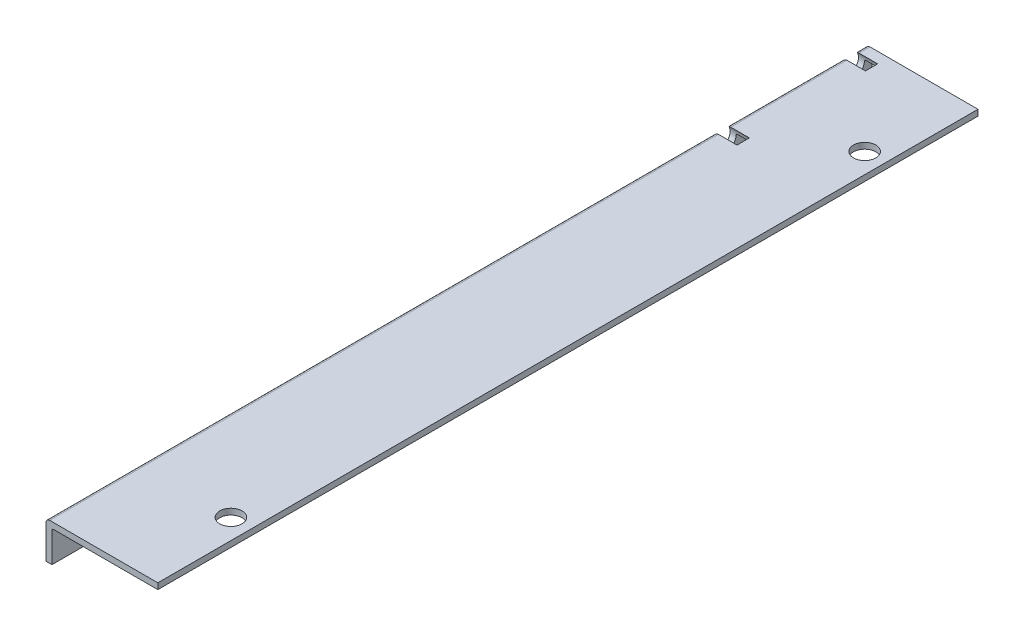
SolidWorks part; units mm, degrees
ref_plane "前视基准面" through (0, 0, 0) normal (0, 0, 1) x (1, 0, 0)
ref_plane "上视基准面" through (0, 0, 0) normal (0, 1, 0) x (1, 0, 0)
ref_plane "右视基准面" through (0, 0, 0) normal (1, 0, 0) x (0, 0, -1)
sketch "草图1" plane through (0, 0, 0) normal (0, 0, 1) x (1, 0, 0)
  line L0 (0, 0) -> (0, 45)
  line L1 (5, 50) -> (150, 50)
  line L2 (8, 0) -> (8, 40)
  line L3 (10, 42) -> (150, 42)
  line L4 (0, 0) -> (8, 0)
  line L5 (150, 50) -> (150, 42)
  line L6 (0, 0) -> (0, 50) construction
  line L7 (0, 50) -> (150, 50) construction
  line L8 (8, 0) -> (8, 42) construction
  line L9 (8, 42) -> (150, 42) construction
  arc A0 (0, 45) -> (5, 50) centre (5, 45) cw
  arc A1 (8, 40) -> (10, 42) centre (10, 40) cw
  point P10 (0, 50)
  dimension "D4" = 5
  dimension "D5" = 2
  dimension "D1" = 50
  dimension "D2" = 150
  dimension "D3" = 8
extrude "凸台-拉伸1" add sketch "草图1" along normal blind 1100
sketch "草图2" plane through (0, 50, 0) normal (0, 1, 0) x (1, 0, 0)
  circle A0 centre (123, -975) radius 15
  circle A1 centre (123, -125) radius 15
extrude "切除-拉伸1" cut sketch "草图2" against normal blind 10
sketch "草图3" plane through (0, 0, 0) normal (-1, 0, 0) x (0, 0, 1)
  circle A0 centre (283.5433, 25.0225) radius 7
  circle A1 centre (140.9394, 19.7047) radius 7
  circle A2 centre (22.7625, 40.5424) radius 7
  circle A3 centre (194.9106, 40.6509) radius 7
  circle A4 centre (81.851, 30.1235) radius 7
  dimension "D1" = 14
  dimension "D2" = 14
  dimension "D3" = 14
  dimension "D4" = 14
  dimension "D5" = 14
extrude "切除-拉伸2" cut sketch "草图3" against normal blind 10
sketch "草图4" plane through (0, 0, 0) normal (-1, 0, 0) x (0, 0, 1)
  circle A0 centre (22.7625, 40.5424) radius 12.5
  circle A1 centre (194.9106, 40.6509) radius 12.5
  dimension "D1" = 25
  dimension "D2" = 25
extrude "切除-拉伸3" cut sketch "草图4" against normal blind 30
sketch "草图5" plane through (0, 0, 0) normal (-1, 0, 0) x (0, 0, 1)
  line L0 (283.5433, 25.0225) -> (960.8976, 25.0225) construction
  line L1 (1100, 45) -> (1100, 0) construction
  circle A0 centre (1000, 25.0225) radius 7
  circle A1 centre (700, 25.0225) radius 7
  dimension "D1" = 100
  dimension "D2" = 300
  dimension "D3" = 14
  dimension "D4" = 14
extrude "切除-拉伸4" cut sketch "草图5" against normal blind 10
